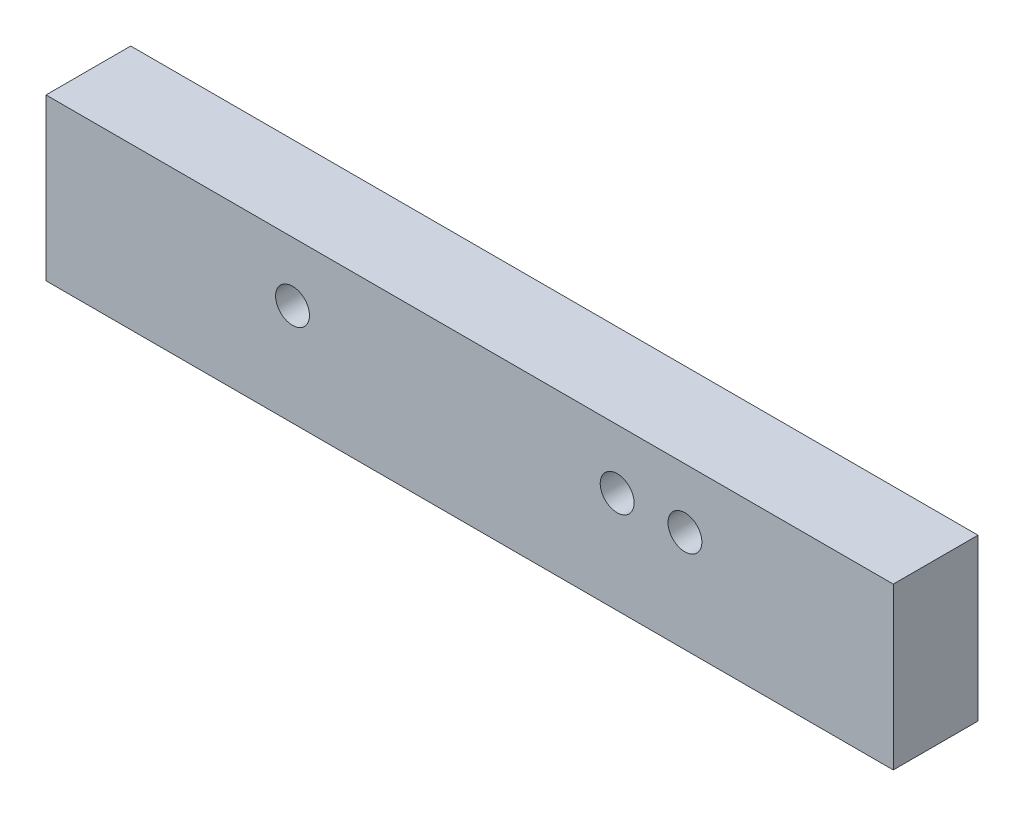
SolidWorks part; units mm, degrees
ref_plane "Front Plane" through (0, 0, 0) normal (0, 0, 1) x (1, 0, 0)
ref_plane "Top Plane" through (0, 0, 0) normal (0, 1, 0) x (1, 0, 0)
ref_plane "Right Plane" through (0, 0, 0) normal (1, 0, 0) x (0, 0, -1)
sketch "Sketch1" plane through (0, 10, 0) normal (0, 1, 0) x (1, 0, 0)
  line L0 (27.2376, -51) -> (27.2376, -46) construction
  line L1 (27.2376, -46) -> (-22.7624, -46) construction
  line L2 (-22.7624, -46) -> (-22.7624, -51) construction
  line L3 (27.2376, -51) -> (27.2376, -46)
  line L4 (27.2376, -46) -> (-22.7624, -46)
  line L5 (-22.7624, -46) -> (-22.7624, -51)
  line L6 (-22.7624, -51) -> (27.2376, -51)
extrude "Boss-Extrude1" add sketch "Sketch1" along normal blind 9.5
sketch "Sketch2" plane through (0, 0, 46) normal (0, 0, -1) x (-1, 0, 0)
  circle A0 centre (-14.9429, 16) radius 1
  circle A2 centre (8.2136, 16) radius 1
  circle A3 centre (-10.9429, 16) radius 1
  point P0 (8.2136, 16)
  point P2 (-11.7864, 16)
  point P4 (-14.9429, 16)
  dimension "D1" = 2
  dimension "D2" = 2
  dimension "D3" = 4
extrude "Cut-Extrude1" cut sketch "Sketch2" against normal up to next
